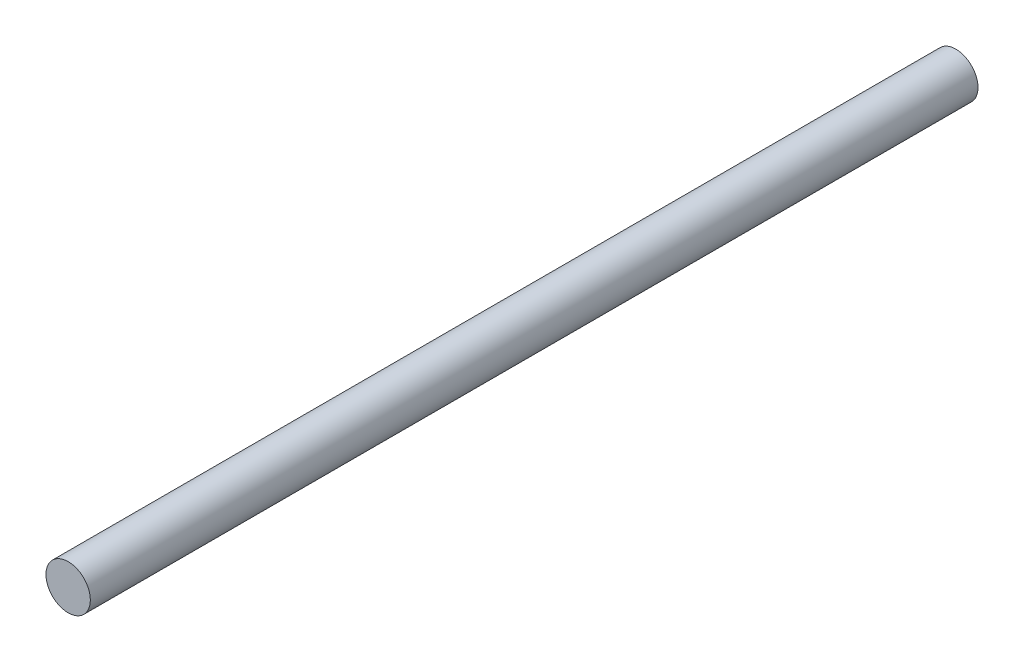
SolidWorks part; units mm, degrees
ref_plane "Front Plane" through (0, 0, 0) normal (0, 0, 1) x (1, 0, 0)
ref_plane "Top Plane" through (0, 0, 0) normal (0, 1, 0) x (1, 0, 0)
ref_plane "Right Plane" through (0, 0, 0) normal (1, 0, 0) x (0, 0, -1)
sketch "Sketch1" plane through (0, 0, 0) normal (0, 0, 1) x (1, 0, 0)
  circle A0 centre (0, 0) radius 2.5
  dimension "D1" = 5
extrude "Boss-Extrude2" add sketch "Sketch1" along normal blind 100 contours A0
